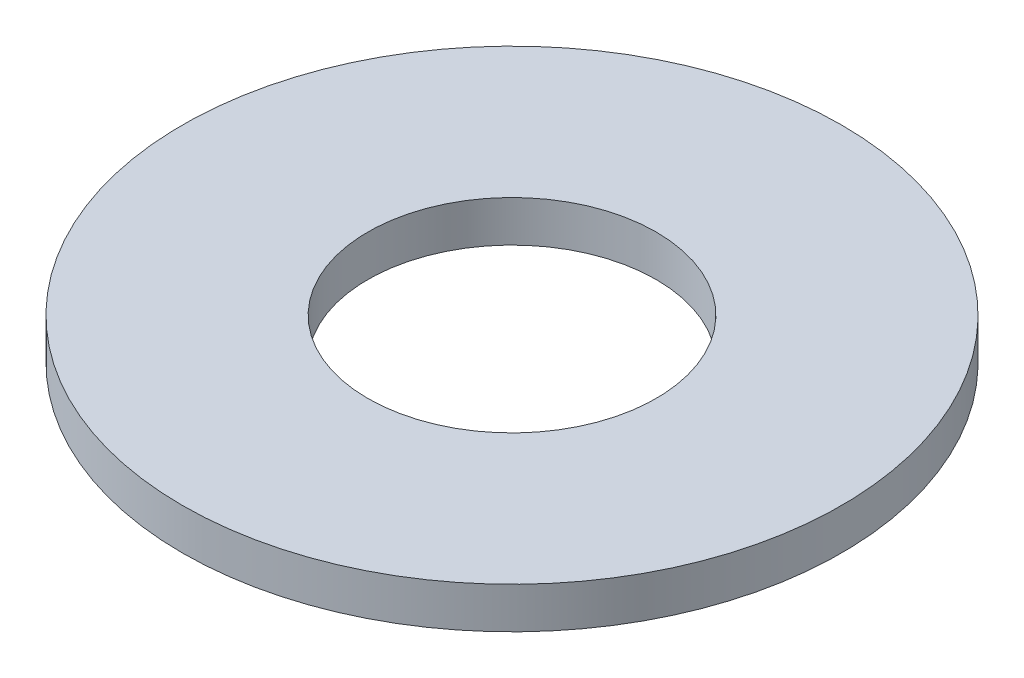
SolidWorks part; units mm, degrees
ref_plane "Front" through (0, 0, 0) normal (0, 0, 1) x (1, 0, 0)
ref_plane "Top" through (0, 0, 0) normal (0, 1, 0) x (1, 0, 0)
ref_plane "Right" through (0, 0, 0) normal (1, 0, 0) x (0, 0, -1)
sketch "Sketch1" plane through (0, 0, 0) normal (0, 1, 0) x (1, 0, 0)
  circle A0 centre (0, 0) radius 8
  circle A1 centre (0, 0) radius 3.5
  dimension "D1" = 7
  dimension "D2" = 16
extrude "Boss-Extrude1" add sketch "Sketch1" along normal blind 1
